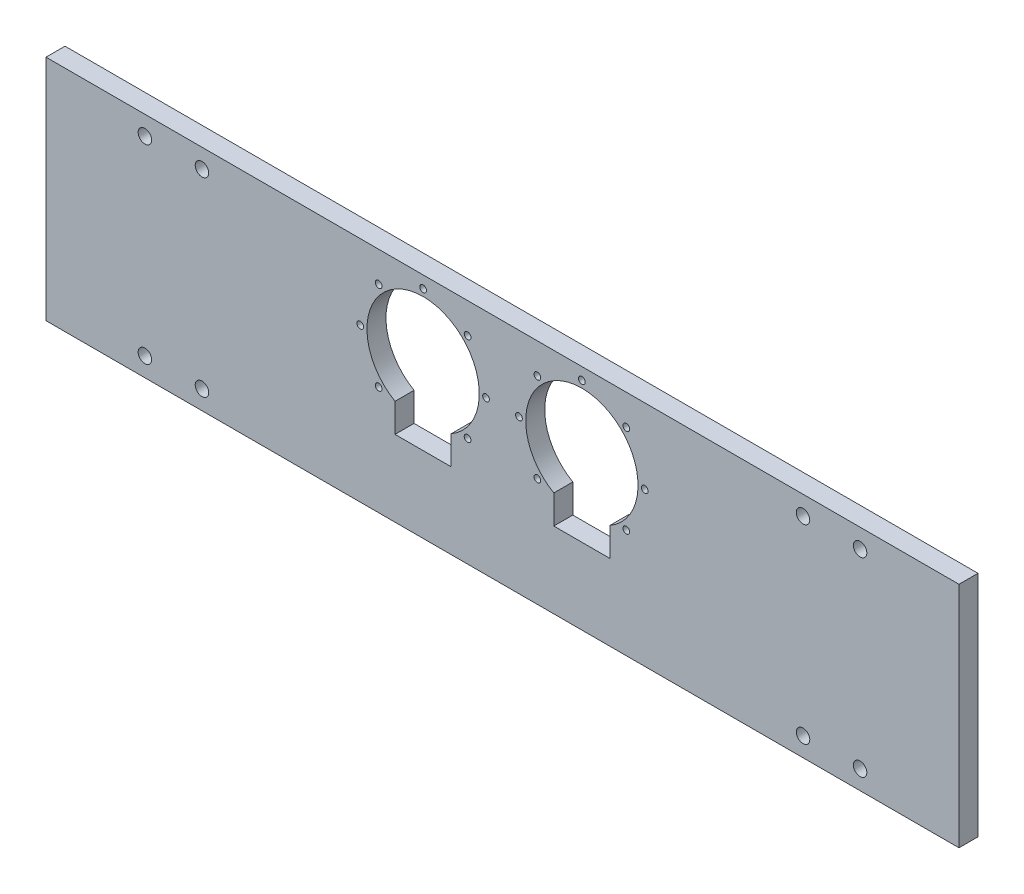
SolidWorks part; units mm, degrees
ref_plane "Front Plane" through (0, 0, 0) normal (0, 0, 1) x (1, 0, 0)
ref_plane "Top Plane" through (0, 0, 0) normal (0, 1, 0) x (1, 0, 0)
ref_plane "Right Plane" through (0, 0, 0) normal (1, 0, 0) x (0, 0, -1)
sketch "Sketch1" plane through (0, 0, 0) normal (0, 0, 1) x (1, 0, 0)
  line L0 (-304.8, 0) -> (304.8, 0) construction
  line L1 (-304.8, 76.2) -> (304.8, 76.2)
  line L2 (-304.8, 76.2) -> (-304.8, -76.2)
  line L3 (-304.8, -76.2) -> (304.8, -76.2)
  line L4 (304.8, 76.2) -> (304.8, -76.2)
  line L5 (-304.8, 76.2) -> (304.8, -76.2) construction
  line L6 (-304.8, -76.2) -> (304.8, 76.2) construction
  line L7 (0, 76.2) -> (0, -76.2) construction
  line L8 (53, 26.2) -> (53, -11.3) construction
  line L9 (53, 26.2) -> (34.25, -6.276) construction
  line L10 (53, 26.2) -> (71.75, -6.276) construction
  line L11 (34.25, -6.276) -> (34.25, -25.4)
  line L12 (71.75, -6.276) -> (71.75, -25.4)
  line L13 (71.75, -25.4) -> (34.25, -25.4)
  line L14 (238.76, 76.2) -> (238.76, -76.2) construction
  line L15 (200.66, 76.2) -> (200.66, -76.2) construction
  line L16 (-34.25, -6.276) -> (-34.25, -25.4)
  line L17 (-71.75, -25.4) -> (-34.25, -25.4)
  line L18 (-71.75, -6.276) -> (-71.75, -25.4)
  circle A5 centre (53, 26.2) radius 48 construction
  arc A6 (71.75, -6.276) -> (34.25, -6.276) centre (53, 26.2) ccw
  circle A7 centre (53, 26.2) radius 42 construction
  circle A8 centre (53, 68.2) radius 2.246
  circle A9 centre (82.6985, 55.8985) radius 2.246
  circle A10 centre (95, 26.2) radius 2.246
  circle A11 centre (82.6985, -3.4985) radius 2.246
  circle A13 centre (23.3015, -3.4985) radius 2.246
  circle A14 centre (11, 26.2) radius 2.246
  circle A15 centre (23.3015, 55.8985) radius 2.246
  arc A16 (55.2454, -15.7465) -> (50.7546, -15.7465) centre (53, -15.8) ccw [skipped]
  circle A17 centre (238.76, 63.5) radius 4.5085
  circle A18 centre (200.66, 63.5) radius 4.5085
  circle A19 centre (238.76, -63.5) radius 4.5085
  circle A20 centre (200.66, -63.5) radius 4.5085
  circle A21 centre (-82.6985, -3.4985) radius 2.246
  circle A22 centre (-95, 26.2) radius 2.246
  circle A23 centre (-82.6985, 55.8985) radius 2.246
  circle A24 centre (-53, 68.2) radius 2.246
  circle A25 centre (-23.3015, 55.8985) radius 2.246
  circle A26 centre (-11, 26.2) radius 2.246
  circle A27 centre (-23.3015, -3.4985) radius 2.246
  arc A28 (-71.75, -6.276) -> (-34.25, -6.276) centre (-53, 26.2) cw
  circle A29 centre (-238.76, 63.5) radius 4.5085
  circle A30 centre (-200.66, 63.5) radius 4.5085
  circle A31 centre (-200.66, -63.5) radius 4.5085
  circle A32 centre (-238.76, -63.5) radius 4.5085
  point P0 (0, 0)
  point P32 (53, 26.2)
  dimension "D3" = 96
  dimension "D6" = 75
  dimension "D7" = 84
  dimension "D8" = 4.492
  dimension "D15" = 9.017
  dimension "D17" = 9.017
  dimension "D1" = 609.6
  dimension "D2" = 152.4
  dimension "D4" = 53
  dimension "D5" = 50
  dimension "D10" = 30
  dimension "D11" = 30
  dimension "D12" = 50.8
  dimension "D13" = 66.04
  dimension "D14" = 38.1
  dimension "D16" = 12.7
  dimension "D18" = 12.7
  dimension "D9" = 8
extrude "Boss-Extrude1" add sketch "Sketch1" along normal blind 12.7
equation "\"bplate_length\"= 24in"
equation "\"bplate_height\"= 6in"
equation "\"bplate_thickness\"= 0.5in"
equation "\"motor_diameter\"= 96 / 25.4in"
equation "\"motor_clearance\"= 5 / 25.4in"
equation "\"motor_mount_hole_pattern_dia\"= 84 / 25.4in"
equation "\"motor_mount_hole_dia\"= 5 / 25.4in"
equation "\"motor_cx\"= \"motor_clearance\" + \"motor_diameter\" / 2in"
equation "\"motor_cy_top\"= \"motor_mount_hole_pattern_dia\" / 2 + \"motor_mount_hole_dia\" * 2in"
equation "\"D1@Sketch1\"=\"bplate_length\""
equation "\"D2@Sketch1\"=\"bplate_height\""
equation "\"motor_driver_cover_dia\"= 75 / 25.4in"
equation "\"D4@Sketch1\"=\"motor_cx\""
equation "\"motor_driver_cutout_clearance\"= 60deg"
equation "\"wire_cutout_clearance\"= 2in"
equation "\"connector_plate_thickness\"= 1in"
equation "\"connector_plate_hole_diameter\"= 0.375in"
equation "\"connector_plate_hole_depth\"= 1in"
equation "\"coonector_first_hole_offset\"= 1.6in"
equation "\"D14@Sketch1\"=1.5"
equation "\"D13@Sketch1\"=\"coonector_first_hole_offset\"+1in"
equation "\"D12@Sketch1\"=\"wire_cutout_clearance\""
equation "\"D16@Sketch1\"=\"connector_plate_thickness\"/2"
equation "\"D18@Sketch1\"=\"connector_plate_thickness\"/2"
equation "\"D15@Sketch1\"=\"connector_plate_hole_diameter\"- 0.02"
equation "\"D17@Sketch1\"=\"connector_plate_hole_diameter\"-0.02"
equation "\"D8@Sketch1\"=\"motor_mount_hole_dia\" - 0.02"
equation "\"D6@Sketch1\"=\"motor_driver_cover_dia\""
equation "\"D7@Sketch1\"=\"motor_mount_hole_pattern_dia\""
